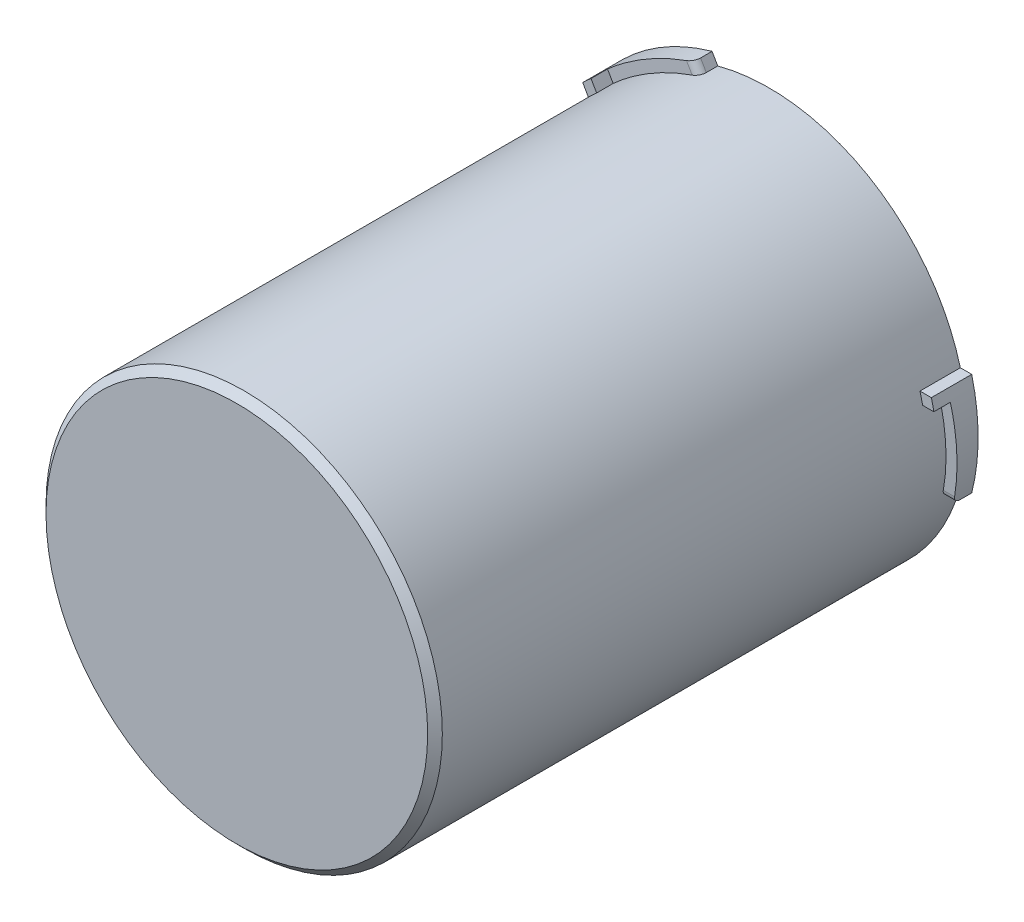
SolidWorks part; units mm, degrees
ref_plane "Спереди" through (0, 0, 0) normal (0, 0, 1) x (1, 0, 0)
ref_plane "Сверху" through (0, 0, 0) normal (0, 1, 0) x (1, 0, 0)
ref_plane "Справа" through (0, 0, 0) normal (1, 0, 0) x (0, 0, -1)
other "Configuration Table"
sketch "Эскиз1" plane through (0, 0, 0) normal (0, 1, 0) x (1, 0, 0)
  line L6 (0, 0) -> (-54, 0)
  line L7 (-54, 0) -> (-54, 145)
  line L8 (-54, 145) -> (-51, 145)
  line L9 (-51, 145) -> (-51, 3)
  line L10 (-51, 3) -> (0, 3)
  line L11 (0, 3) -> (0, 0)
  dimension "D1" = 3
  dimension "D2" = 3
  dimension "D3" = 145
  dimension "D4" = 54
revolve "Повернуть1" add sketch "Эскиз1" angle 360 about L11
ref_plane "Плоскость2" through (57, 0, 0) normal (1, 0, 0) x (0, 0, -1)
sketch "Эскиз2" plane through (57, 0, 0) normal (1, 0, 0) x (0, 0, -1)
  line L0 (145, 14) -> (145, -14)
  line L1 (145, -54) -> (145, 54) construction
  line L2 (145, -14) -> (140, -14)
  line L3 (140, -14) -> (138.5, 11)
  line L4 (138.5, 11) -> (134, 11)
  line L5 (134, 11) -> (134, 14)
  line L6 (134, 14) -> (145, 14)
  point P8 (0, 0)
  dimension "D1" = 28
  dimension "D2" = 3
  dimension "D3" = 6.5
  dimension "D4" = 11
  dimension "D5" = 5
  dimension "D6" = 14
extrude "Бобышка-Вытянуть1" add sketch "Эскиз2" against normal blind 10
fillet "Скругление1" radius 2 1 edges at (54.5768, -14, -140)
pattern_circular "Круговой массив2" count 3 over 360 about axis through (0, 0, 0) along (0, 0, 1) of "Бобышка-Вытянуть1", "Скругление1"
sketch "Эскиз3" plane through (0, 0, -145) normal (0, 0, -1) x (-1, 0, 0)
  circle A0 centre (0, 0) radius 51
extrude "Вырез-Вытянуть1" cut sketch "Эскиз3" against normal blind 15
sketch "Эскиз4" plane through (0, 0, -145) normal (0, 0, -1) x (-1, 0, 0)
  circle A0 centre (0, 0) radius 57
  circle A1 centre (0, 0) radius 62.6187
extrude "Вырез-Вытянуть2" cut sketch "Эскиз4" against normal blind 15
chamfer "Фаска1" distance 2 angle 45 1 edges at (-54, 0, 0)
sketch "Эскиз5" plane through (0, 0, 0) normal (0, 0, 1) x (1, 0, 0)
  circle A0 centre (0, 0) radius 42.5
  dimension "D1" = 85
fillet "Скругление2" radius 5 1 edges at (-51, 0, -3)
equation "\"d\"=3"
equation "\"D1@Эскиз1\"=\"d\""
equation "\"D2@Эскиз1\"=\"d\""
